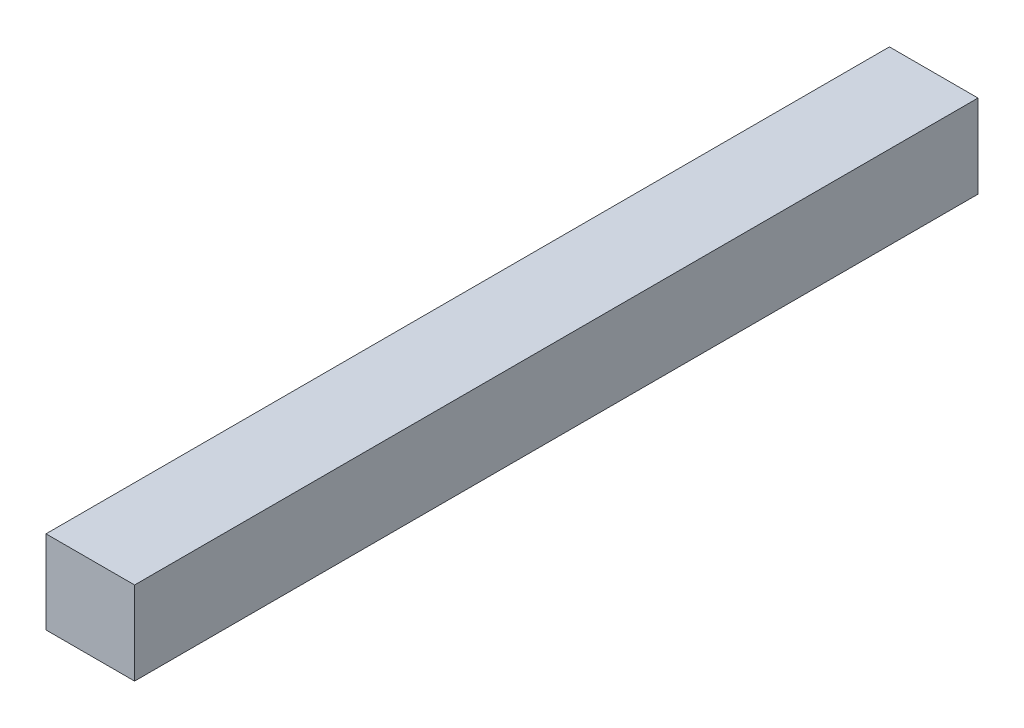
SolidWorks part; units mm, degrees
ref_plane "Front Plane" through (0, 0, 0) normal (0, 0, 1) x (1, 0, 0)
ref_plane "Top Plane" through (0, 0, 0) normal (0, 1, 0) x (1, 0, 0)
ref_plane "Right Plane" through (0, 0, 0) normal (1, 0, 0) x (0, 0, -1)
sketch "Sketch1" plane through (0, 0, 0) normal (0, 0, 1) x (1, 0, 0)
  line L9 (-2683.7143, 1702.5714) -> (-2633.7143, 1702.5714)
  line L10 (-2683.7143, 1702.5714) -> (-2683.7143, 1655.5714)
  line L11 (-2683.7143, 1655.5714) -> (-2633.7143, 1655.5714)
  line L12 (-2633.7143, 1702.5714) -> (-2633.7143, 1655.5714)
  dimension "D1" = 50
  dimension "D2" = 47
extrude "Boss-Extrude1" add sketch "Sketch1" along normal blind 476
